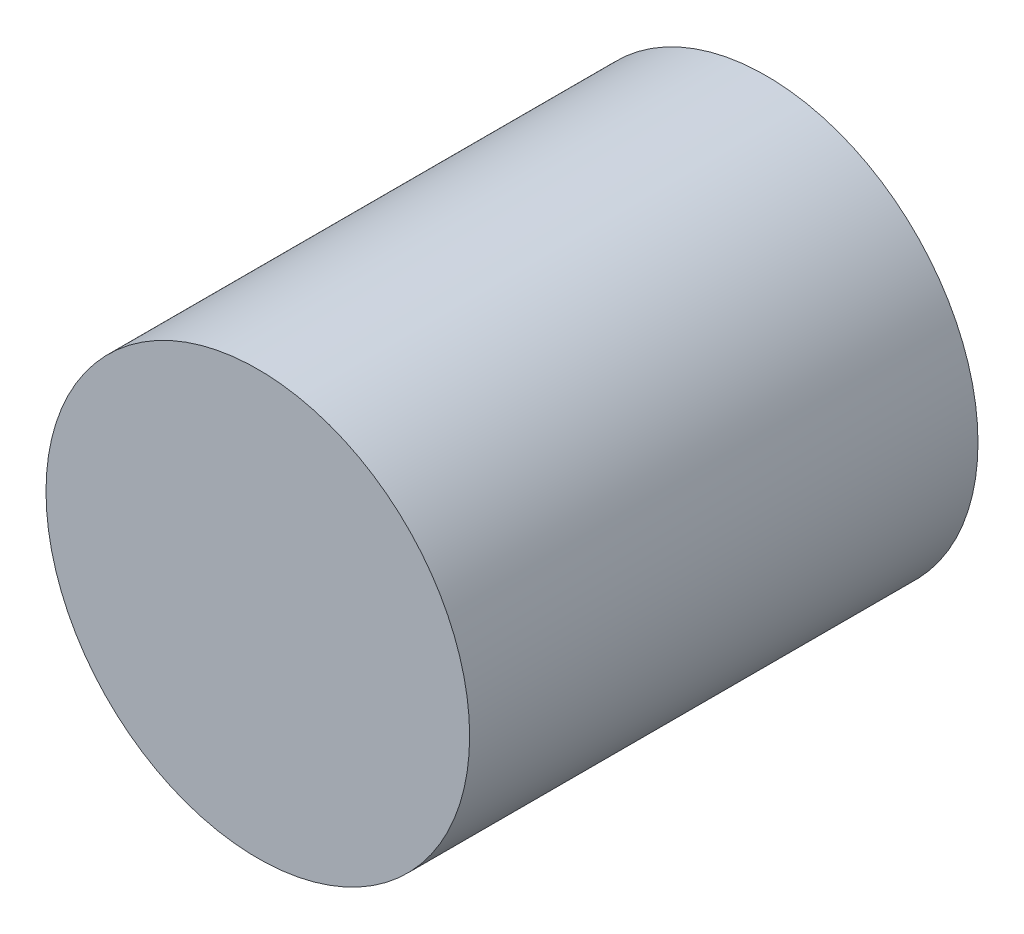
SolidWorks part; units mm, degrees
ref_plane "Front Plane" through (0, 0, 0) normal (0, 0, 1) x (1, 0, 0)
ref_plane "Top Plane" through (0, 0, 0) normal (0, 1, 0) x (1, 0, 0)
ref_plane "Right Plane" through (0, 0, 0) normal (1, 0, 0) x (0, 0, -1)
sketch "Sketch1" plane through (0, 0, 0) normal (0, 0, 1) x (1, 0, 0)
  circle A0 centre (0, 0) radius 5
  dimension "D1" = 10
extrude "Boss-Extrude1" add sketch "Sketch1" along normal blind 12
